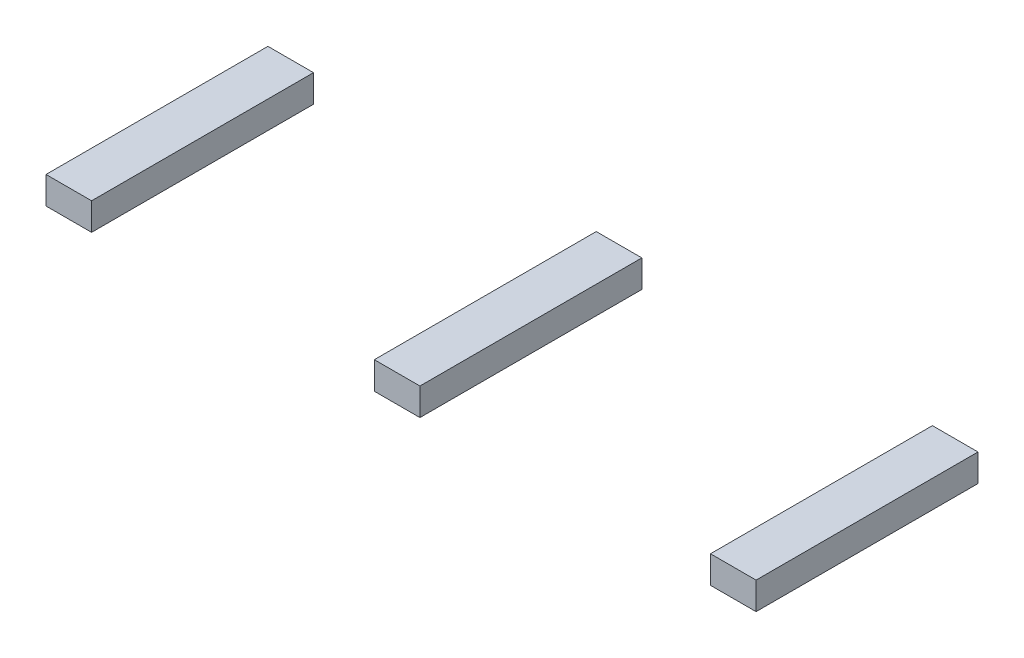
SolidWorks part; units mm, degrees
ref_plane "Alzado" through (0, 0, 0) normal (0, 0, 1) x (1, 0, 0)
ref_plane "Planta" through (0, 0, 0) normal (0, 1, 0) x (1, 0, 0)
ref_plane "Vista lateral" through (0, 0, 0) normal (1, 0, 0) x (0, 0, -1)
sketch "Croquis1" plane through (0, 0, 0) normal (0, 0, 1) x (1, 0, 0)
  line L0 (-6.35, 2.9) -> (-6.35, -2.9) construction
  line L1 (-6.35, 2.9) -> (-6.35, -2.9) construction
  line L2 (-4.6, 2.9) -> (-6.35, 2.9) construction
  line L3 (-4.6, 2.9) -> (-6.35, 2.9) construction
  line L4 (6.35, 2.9) -> (4.6, 2.9) construction
  line L5 (-5.7752, -0.2867) -> (-5.0252, -0.2867)
  line L6 (-5.7752, -0.2867) -> (-5.7752, 0.1633)
  line L7 (-5.7752, 0.1633) -> (-5.0252, 0.1633)
  line L8 (-5.0252, -0.2867) -> (-5.0252, 0.1633)
  line L9 (-5.7752, -0.2867) -> (-5.0252, 0.1633) construction
  line L10 (-5.7752, 0.1633) -> (-5.0252, -0.2867) construction
  line L11 (-0.375, -0.225) -> (0.375, -0.225)
  line L12 (-0.375, -0.225) -> (-0.375, 0.225)
  line L13 (-0.375, 0.225) -> (0.375, 0.225)
  line L14 (0.375, -0.225) -> (0.375, 0.225)
  line L15 (-0.375, -0.225) -> (0.375, 0.225) construction
  line L16 (-0.375, 0.225) -> (0.375, -0.225) construction
  line L17 (6.35, 2.9) -> (4.6, 2.9) construction
  line L19 (5.9039, -0.225) -> (5.1539, -0.225)
  line L20 (5.9039, -0.225) -> (5.9039, 0.225)
  line L21 (5.9039, 0.225) -> (5.1539, 0.225)
  line L22 (5.1539, -0.225) -> (5.1539, 0.225)
  line L23 (5.9039, -0.225) -> (5.1539, 0.225) construction
  line L24 (5.9039, 0.225) -> (5.1539, -0.225) construction
  point P3 (-5.4002, -0.0617)
  point P8 (0, 0)
  point P16 (5.5289, 0)
  dimension "D1" = 0.75
  dimension "D2" = 0.45
  dimension "D3" = 0.45
  dimension "D4" = 0.75
  dimension "D5" = 0.75
  dimension "D6" = 0.45
extrude "Saliente-Extruir1" add sketch "Croquis1" along normal blind 3.65
